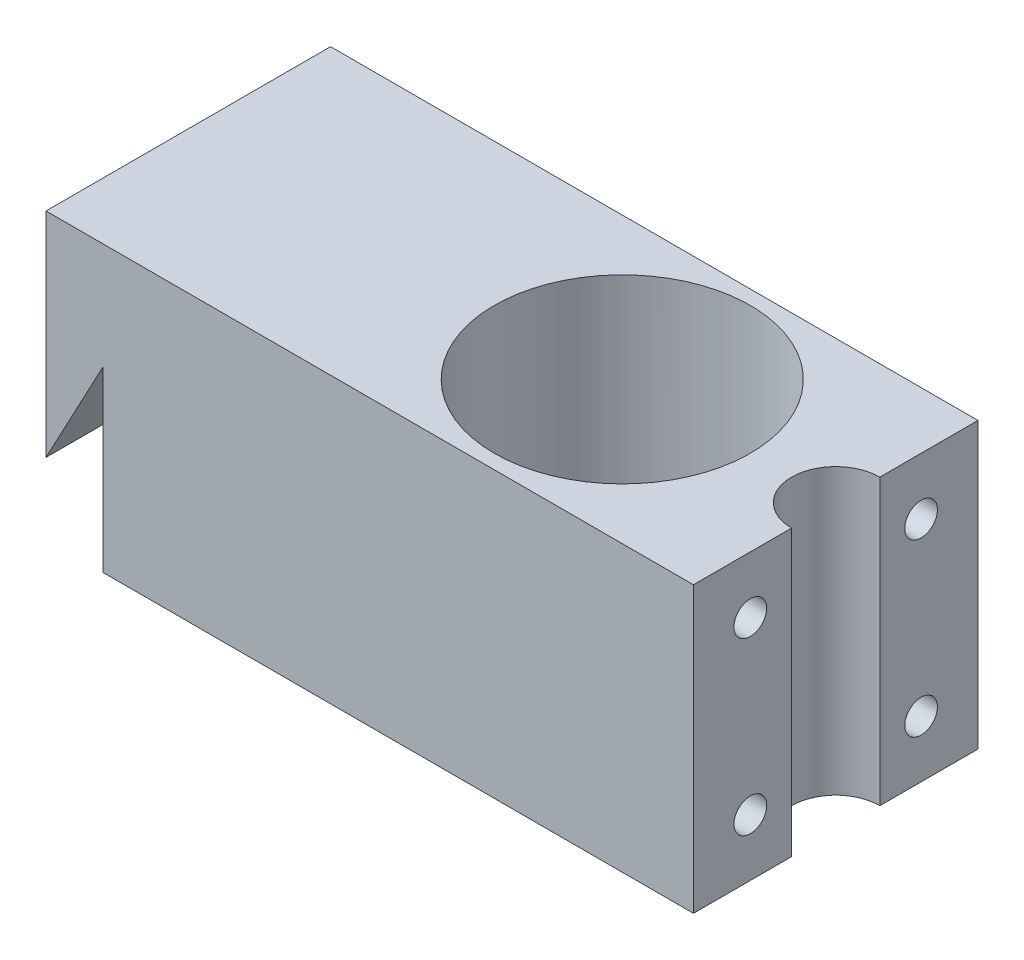
SolidWorks part; units mm, degrees
ref_plane "Front Plane" through (0, 0, 0) normal (0, 0, 1) x (1, 0, 0)
ref_plane "Top Plane" through (0, 0, 0) normal (0, 1, 0) x (1, 0, 0)
ref_plane "Right Plane" through (0, 0, 0) normal (1, 0, 0) x (0, 0, -1)
sketch "Sketch2" plane through (0, 0, 0) normal (0, 0, 1) x (1, 0, 0)
  line L0 (-16, -10) -> (25.5, -10)
  line L1 (25.5, -10) -> (25.5, 10)
  line L2 (25.5, 10) -> (-20, 10)
  line L3 (-20, 10) -> (-20, -5)
  line L4 (-20, -5) -> (-16, 2.5)
  line L5 (-16, 2.5) -> (-16, -10)
  line L6 (18, 10) -> (18, -84.1476) construction
  line L19 (-20, -147.824) -> (56, -147.824) construction
  line L20 (-20, 17.5) -> (-20, -5) construction
  line L27 (-20, -2.824) -> (-20, -147.824) construction
  point P11 (25.5, 0)
  point P18 (18, -147.824)
  dimension "D1" = 20
  dimension "D2" = 7.5
  dimension "D3" = 4
  dimension "D4" = 5
  dimension "D5" = 7.5
extrude "Boss-Extrude1" add sketch "Sketch2" along normal mid plane 20
sketch "Sketch3" plane through (0, 10, 0) normal (0, 1, 0) x (1, 0, 0)
  line L0 (25.5, -10) -> (25.5, 10) construction
  circle A0 centre (10.5, 0) radius 9
  circle A1 centre (25.5, 0) radius 3.1
  dimension "D1" = 6.2
  dimension "D2" = 18
  dimension "D3" = 15
extrude "Cut-Extrude1" cut sketch "Sketch3" against normal up to next
sketch "Sketch4" plane through (25.5, 0, 0) normal (1, 0, 0) x (0, 0, -1)
  line L0 (-10, -10) -> (-10, 10) construction
  line L1 (3.1, -10) -> (10, -10) construction
  line L2 (10, -10) -> (10, 10) construction
  circle A0 centre (-6, 6) radius 1.15
  circle A1 centre (-6, -6) radius 1.15
  circle A2 centre (6, -6) radius 1.15
  circle A3 centre (6, 6) radius 1.15
  dimension "D5" = 2.3
  dimension "D1" = 4
  dimension "D2" = 4
  dimension "D3" = 4
  dimension "D4" = 4
extrude "Cut-Extrude2" cut sketch "Sketch4" against normal blind 10
